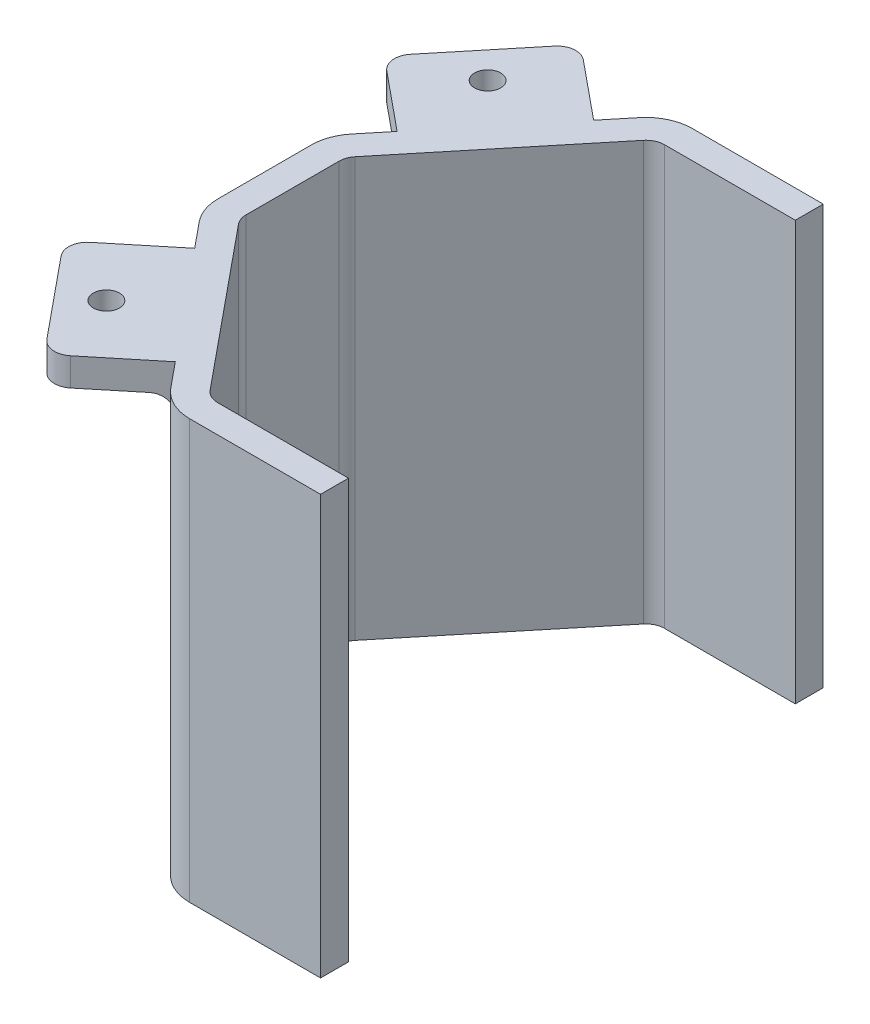
SolidWorks part; units mm, degrees
ref_plane "Front Plane" through (0, 0, 0) normal (0, 0, 1) x (1, 0, 0)
ref_plane "Top Plane" through (0, 0, 0) normal (0, 1, 0) x (1, 0, 0)
ref_plane "Right Plane" through (0, 0, 0) normal (1, 0, 0) x (0, 0, -1)
sketch "Sketch2" plane through (0, 0, 0) normal (0, 1, 0) x (1, 0, 0)
  line L0 (-6, 30) -> (6, 30)
  line L1 (6, 30) -> (6, 24)
  line L2 (6, 24) -> (2, 24)
  line L3 (2, 24) -> (2, -24)
  line L4 (2, -24) -> (6, -24)
  line L5 (6, -24) -> (6, -30)
  line L6 (6, -30) -> (-6, -30)
  line L7 (-6, -30) -> (-6, -24)
  line L8 (-6, -24) -> (-2, -24)
  line L9 (-2, -24) -> (-2, 24)
  line L10 (-2, 24) -> (-6, 24)
  line L11 (-6, 24) -> (-6, 30)
  dimension "D2" = 60
  dimension "D3" = 6
  dimension "D4" = 4
sketch "Sketch3" plane through (0, 0, 0) normal (0, 1, 0) x (1, 0, 0)
  line L0 (-8, 24) -> (-22.0538, 24)
  line L1 (-23.6001, 23.2685) -> (-37.5463, 6.2685)
  line L2 (-38, 5) -> (-38, -5)
  line L3 (-37.5463, -6.2685) -> (-23.6001, -23.2685)
  line L4 (-22.0538, -24) -> (-8, -24)
  line L5 (-8, 24) -> (-8, -24) construction
  line L7 (-2, 24) -> (-6, 24) construction
  line L8 (-8, 24) -> (-23, 24) construction
  line L9 (-8, 27) -> (-22.0538, 27)
  line L10 (-25.9195, 25.1712) -> (-39.8657, 8.1712)
  line L11 (-41, 5) -> (-41, -5)
  line L12 (-39.8657, -8.1712) -> (-25.9195, -25.1712)
  line L13 (-22.0538, -27) -> (-8, -27)
  line L14 (-8, 27) -> (-8, 24)
  line L15 (-8, -27) -> (-8, -24)
  line L16 (-23, 24) -> (-38, 5.7154) construction
  line L17 (-23, -24) -> (-8, -24) construction
  line L18 (-38, -5.7154) -> (-23, -24) construction
  line L19 (-24.4192, -27) -> (-8, -27) construction
  line L20 (-41, -6.7885) -> (-24.4192, -27) construction
  line L21 (-8, 27) -> (-24.4192, 27) construction
  line L22 (-24.4192, 27) -> (-41, 6.7885) construction
  line L23 (-38, 5.7154) -> (-38, -5.7154) construction
  line L24 (-41, 6.7885) -> (-41, -6.7885) construction
  arc A0 (-22.0538, 24) -> (-23.6001, 23.2685) centre (-22.0538, 22) ccw
  arc A1 (-22.0538, -24) -> (-23.6001, -23.2685) centre (-22.0538, -22) cw
  arc A2 (-22.0538, -27) -> (-25.9195, -25.1712) centre (-22.0538, -22) cw
  arc A3 (-22.0538, 27) -> (-25.9195, 25.1712) centre (-22.0538, 22) ccw
  arc A4 (-37.5463, 6.2685) -> (-38, 5) centre (-36, 5) ccw
  arc A5 (-37.5463, -6.2685) -> (-38, -5) centre (-36, -5) cw
  arc A6 (-41, 5) -> (-39.8657, 8.1712) centre (-36, 5) cw
  arc A7 (-39.8657, -8.1712) -> (-41, -5) centre (-36, -5) cw
  point P2 (-8, 0)
  point P7 (-38, 0)
  point P21 (-23, 24)
  point P25 (-23, -24)
  dimension "D6" = 2
  dimension "D7" = 2
  dimension "D8" = 5
  dimension "D9" = 5
  dimension "D10" = 2
  dimension "D4" = 2
  dimension "D12" = 5
  dimension "D13" = 5
  dimension "D1" = 2
  dimension "D2" = 15
  dimension "D3" = 30
  dimension "D11" = 10
  dimension "D5" = 3
extrude "Boss-Extrude1" add sketch "Sketch3" along normal blind 45
sketch "Sketch4" plane through (0, 45, 0) normal (0, -1, 0) x (1, 0, 0)
  line L0 (-28.1357, 22.4697) -> (-35.867, 28.8122)
  line L1 (-39.8657, 8.1712) -> (-25.9195, 25.1712) construction
  line L2 (-35.867, 28.8122) -> (-45.3807, 17.2152)
  line L3 (-45.3807, 17.2152) -> (-37.6494, 10.8728)
  line L4 (-28.1357, 22.4697) -> (-37.6494, 10.8728)
  line L5 (-37.6494, -10.8728) -> (-45.3807, -17.2152)
  line L6 (-25.9195, -25.1712) -> (-39.8657, -8.1712) construction
  line L7 (-45.3807, -17.2152) -> (-35.867, -28.8122)
  line L8 (-35.867, -28.8122) -> (-28.1357, -22.4697)
  line L9 (-28.1357, -22.4697) -> (-37.6494, -10.8728)
  point P7 (-32.8926, -16.6712)
  point P8 (-32.8926, -16.6712)
  point P21 (-32.8926, 16.6712)
  point P22 (-32.8926, 16.6712)
  dimension "D1" = 10
  dimension "D2" = 10
  dimension "D3" = 15
  dimension "D4" = 15
extrude "Boss-Extrude2" add sketch "Sketch4" along normal blind 3
fillet "Fillet1" radius 2 6 edges at (-32.8926, 42, -16.6712) (-35.867, 43.5, -28.8122) (-45.3807, 43.5, -17.2152) (-32.8926, 42, 16.6712) (-35.867, 43.5, 28.8122) (-45.3807, 43.5, 17.2152)
sketch "Sketch5" plane through (0, 42, 0) normal (0, -1, 0) x (1, 0, 0)
  line L0 (-43.8345, 15.9467) -> (-39.1957, 12.1413) construction
  line L1 (-37.1355, 27.2659) -> (-44.1122, 18.7615) construction
  circle A0 centre (-37.5314, 20.4767) radius 1.4
  dimension "D3" = 2.8
  dimension "D1" = 4
  dimension "D2" = 7.5
extrude "Cut-Extrude1" cut sketch "Sketch5" against normal through all
mirror "Mirror1" about plane through (0, 0, 0) normal (0, 0, 1) of "Cut-Extrude1"
